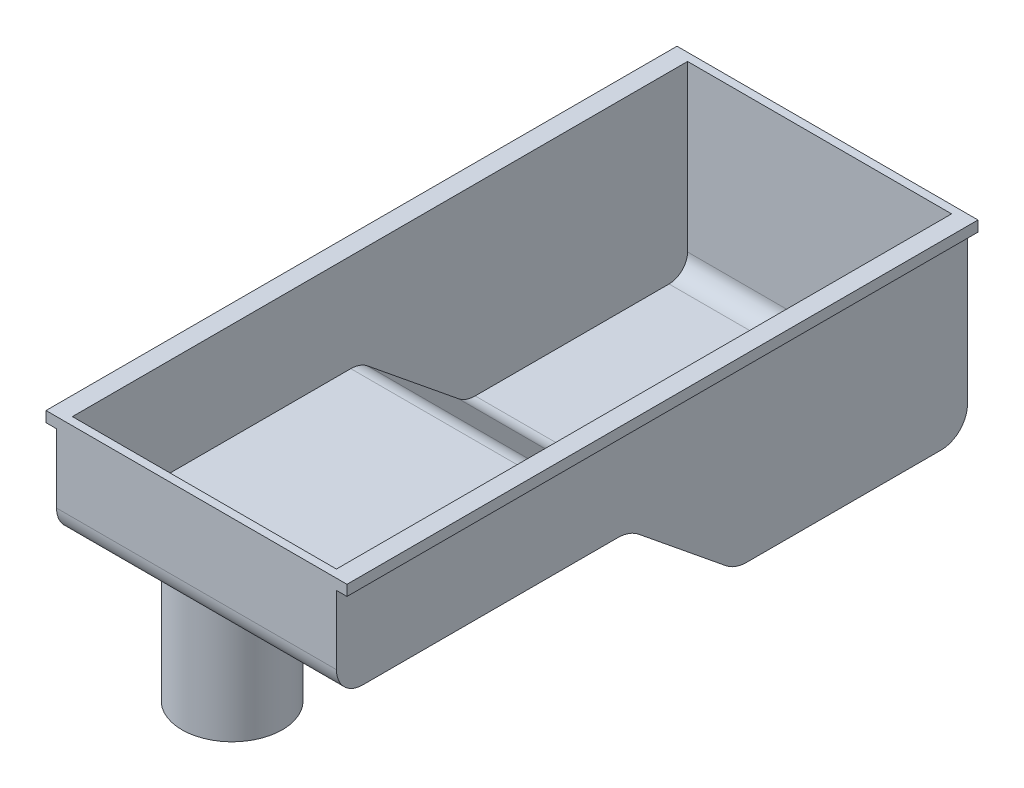
SolidWorks part; units mm, degrees
ref_plane "Front Plane" through (0, 0, 0) normal (0, 0, 1) x (1, 0, 0)
ref_plane "Top Plane" through (0, 0, 0) normal (0, 1, 0) x (1, 0, 0)
ref_plane "Right Plane" through (0, 0, 0) normal (1, 0, 0) x (0, 0, -1)
other "Configuration Table"
sketch "Sketch1" plane through (0, 0, 0) normal (1, 0, 0) x (0, 0, -1)
  line L0 (-72, -70) -> (406, -70)
  line L1 (406, -70) -> (406, -195)
  line L2 (386, -215) -> (238.876, -215)
  line L3 (223.1112, -209.4029) -> (156.8888, -155.5971)
  line L4 (141.124, -150) -> (-52, -150)
  line L5 (-72, -130) -> (-72, -70)
  arc A0 (406, -195) -> (386, -215) centre (386, -195) cw
  arc A1 (238.876, -215) -> (223.1112, -209.4029) centre (238.876, -190) cw
  arc A2 (156.8888, -155.5971) -> (141.124, -150) centre (141.124, -175) ccw
  arc A3 (-52, -150) -> (-72, -130) centre (-52, -130) cw
extrude "Pan Body" add sketch "Sketch1" along normal blind 212 from offset 106
sketch "Sketch2" plane through (0, 0, 0) normal (0, 0, 1) x (1, 0, 0)
  line L0 (-114, -78) -> (114, -78)
  line L1 (114, -78) -> (114, -70)
  line L2 (114, -70) -> (-114, -70)
  line L3 (-114, -70) -> (-114, -78)
extrude "Pan Rail" add sketch "Sketch2" along normal blind 478 from offset 406
sketch "Sketch3" plane through (0, 0, 0) normal (1, 0, 0) x (0, 0, -1)
  line L0 (-66, -60) -> (400, -60)
  line L1 (400, -60) -> (400, -195)
  line L2 (386, -209) -> (239.1008, -209)
  line L3 (226.489, -204.5223) -> (157.511, -148.4777)
  line L4 (144.8992, -144) -> (-52, -144)
  line L5 (-66, -130) -> (-66, -60)
  arc A0 (400, -195) -> (386, -209) centre (386, -195) cw
  arc A1 (239.1008, -209) -> (226.489, -204.5223) centre (239.1008, -189) cw
  arc A2 (157.511, -148.4777) -> (144.8992, -144) centre (144.8992, -164) ccw
  arc A3 (-52, -144) -> (-66, -130) centre (-52, -130) cw
extrude "Sump" cut sketch "Sketch3" along normal blind 200 from offset 100
sketch "Sketch4" plane through (0, 0, 0) normal (0, 1, 0) x (1, 0, 0)
  circle A0 centre (0, 380) radius 11
extrude "Drain Plug" add sketch "Sketch4" along normal blind 11 from offset 225
sketch "Sketch5" plane through (0, 0, 0) normal (0, 1, 0) x (1, 0, 0)
  circle A0 centre (-45, 0) radius 42
extrude "Filter Adapter" add sketch "Sketch5" along normal blind 11 from offset 160
sketch "Sketch6" plane through (0, 0, 0) normal (0, 1, 0) x (1, 0, 0)
  circle A0 centre (-45, 0) radius 38
extrude "Oil Filter" add sketch "Sketch6" along normal blind 102 from offset 262
